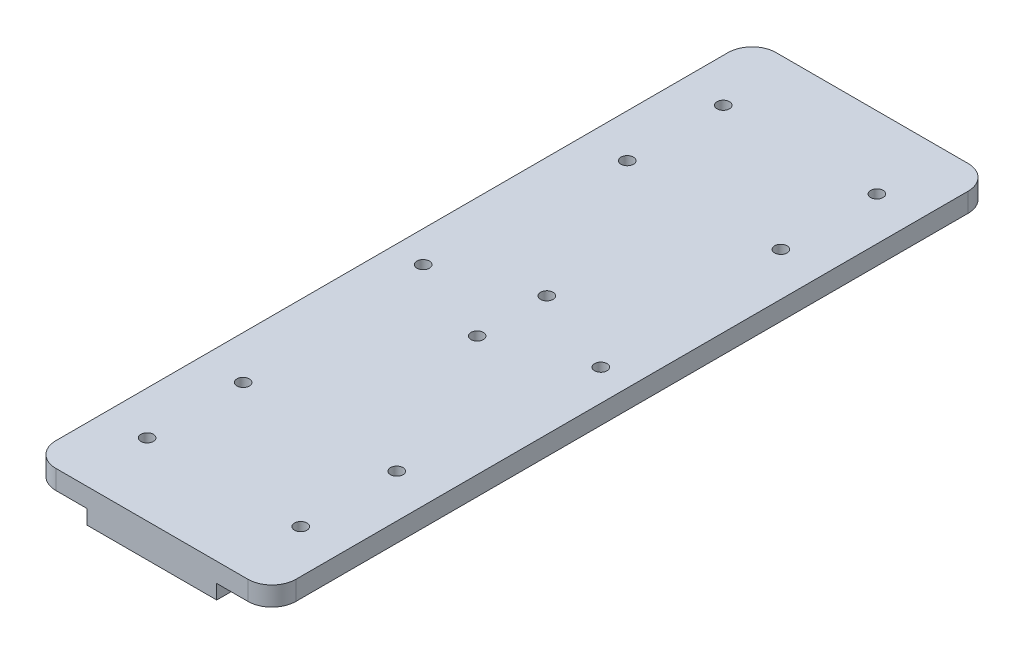
SolidWorks part; units mm, degrees
ref_plane "前视基准面" through (0, 0, 0) normal (0, 0, 1) x (1, 0, 0)
ref_plane "上视基准面" through (0, 0, 0) normal (0, 1, 0) x (1, 0, 0)
ref_plane "右视基准面" through (0, 0, 0) normal (1, 0, 0) x (0, 0, -1)
sketch "草图1" plane through (0, 0, 0) normal (0, 1, 0) x (1, 0, 0)
  line L0 (25, 0) -> (-25, 0) construction
  line L1 (-25, 75) -> (25, 75)
  line L2 (-25, 75) -> (-25, -75)
  line L3 (-25, -75) -> (25, -75)
  line L4 (25, 75) -> (25, -75)
  line L5 (-25, 75) -> (25, -75) construction
  line L6 (-25, -75) -> (25, 75) construction
  line L7 (0, 75) -> (0, -75) construction
  line L8 (0, -7.25) -> (0, 7.25) construction
  line L9 (-18.5, 0) -> (18.5, 0) construction
  line L10 (-16, 40) -> (16, 40) construction
  line L11 (-16, 60) -> (16, 60) construction
  line L12 (-16, -40) -> (16, -40) construction
  line L13 (-16, -60) -> (16, -60) construction
  circle A0 centre (0, 7.25) radius 1.3
  circle A1 centre (0, -7.25) radius 1.3
  circle A2 centre (-18.5, 0) radius 1.3
  circle A3 centre (18.5, 0) radius 1.3
  circle A4 centre (-16, -40) radius 1.3
  circle A5 centre (16, -40) radius 1.3
  circle A6 centre (-16, -60) radius 1.3
  circle A7 centre (16, -60) radius 1.3
  circle A8 centre (-16, 40) radius 1.3
  circle A9 centre (16, 40) radius 1.3
  circle A10 centre (-16, 60) radius 1.3
  circle A11 centre (16, 60) radius 1.3
  point P0 (0, 0)
  point P13 (0, 0)
  point P16 (0, 0)
  point P19 (0, 40)
  point P22 (0, 60)
  point P25 (0, -40)
  point P28 (0, -60)
  dimension "D1" = 50
  dimension "D2" = 150
  dimension "D3" = 14.5
  dimension "D4" = 37
  dimension "D5" = 40
  dimension "D6" = 16
  dimension "D7" = 16
  dimension "D8" = 20
  dimension "D9" = 40
  dimension "D10" = 60
  dimension "D11" = 16
  dimension "D12" = 16
extrude "凸台-拉伸1" add sketch "草图1" along normal blind 4
sketch "草图3" plane through (0, 0, 0) normal (0, -1, 0) x (1, 0, 0)
  line L0 (0, 75) -> (0, -75) construction
  line L1 (-25, 75) -> (25, 75) construction
  line L2 (25, -75) -> (-25, -75) construction
  line L3 (0, -12.5) -> (0, 12.5) construction
  line L4 (-13.5, 12.5) -> (13.5, 12.5) construction
  line L5 (-13.5, -12.5) -> (13.5, -12.5) construction
  line L6 (13.5, 12.5) -> (13.5, 75) construction
  line L7 (13.5, -12.5) -> (13.5, -75) construction
  line L8 (-13.5, 12.5) -> (13.5, 12.5)
  line L9 (-13.5, 12.5) -> (-13.5, 75)
  line L10 (13.5, 12.5) -> (13.5, 75)
  line L11 (-13.5, 75) -> (13.5, 75)
  line L12 (-13.5, -12.5) -> (13.5, -12.5)
  line L13 (-13.5, -12.5) -> (-13.5, -75)
  line L14 (13.5, -12.5) -> (13.5, -75)
  line L15 (-13.5, -75) -> (13.5, -75)
  point P10 (0, 0)
  point P13 (0, 12.5)
  point P16 (0, -12.5)
  dimension "D1" = 25
  dimension "D2" = 27
  dimension "D3" = 27
extrude "凸台-拉伸2" add sketch "草图3" along normal blind 3
fillet "圆角1" radius 5 4 edges at (-25, 2, -75) (25, 2, -75) (25, 2, 75) (-25, 2, 75)
